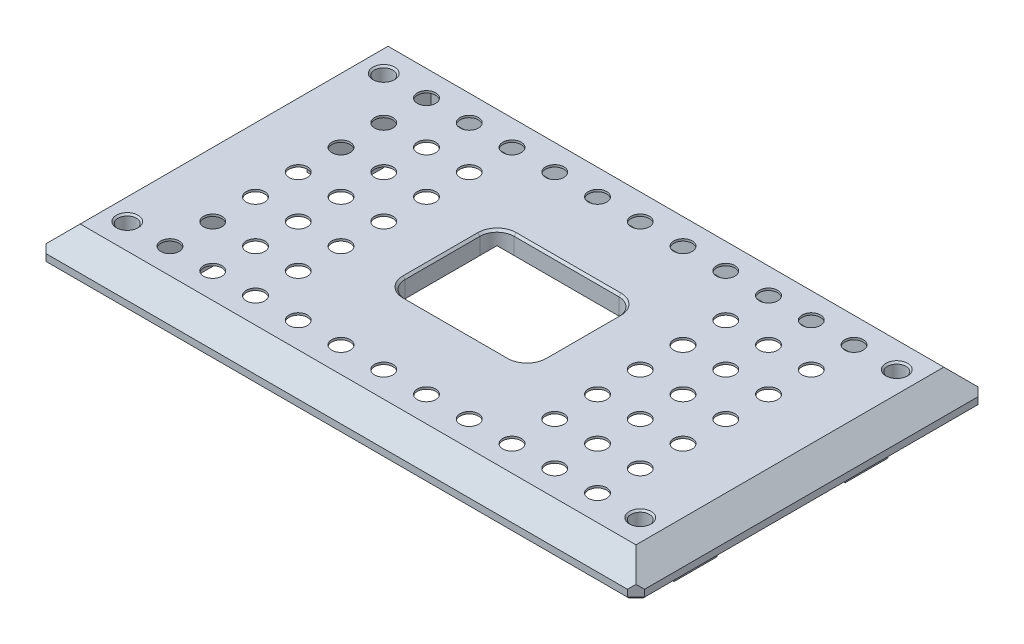
SolidWorks part; units mm, degrees
ref_plane "Front Plane" through (0, 0, 0) normal (0, 0, 1) x (1, 0, 0)
ref_plane "Top Plane" through (0, 0, 0) normal (0, 1, 0) x (1, 0, 0)
ref_plane "Right Plane" through (0, 0, 0) normal (1, 0, 0) x (0, 0, -1)
sketch "Sketch1" plane through (0, 0, 0) normal (0, 1, 0) x (1, 0, 0)
  line L1 (-70, -41) -> (70, -41)
  line L2 (-70, -41) -> (-70, 41)
  line L3 (-70, 41) -> (70, 41)
  line L4 (70, -41) -> (70, 41)
  line L5 (-70, -41) -> (70, 41) construction
  line L6 (-70, 41) -> (70, -41) construction
  point P0 (0, 0)
  dimension "D1" = 140
  dimension "D2" = 82
extrude "Boss-Extrude1" add sketch "Sketch1" along normal blind 2
sketch "Sketch2" plane through (0, 2, 0) normal (0, 1, 0) x (1, 0, 0)
  line L4 (70, -41) -> (70, 41)
  line L5 (70, 41) -> (-70, 41)
  line L6 (-70, 41) -> (-70, -41)
  line L7 (-70, -41) -> (70, -41)
  line L8 (70, -41) -> (70, 41)
  line L9 (70, 41) -> (-70, 41)
  line L10 (-70, 41) -> (-70, -41)
  line L11 (-70, -41) -> (70, -41)
  dimension "D1" = 0
ref_plane "Plane1" through (0, 7, 0) normal (0, 1, 0) x (1, 0, 0)
sketch "Sketch3" plane through (0, 7, 0) normal (0, 1, 0) x (1, 0, 0)
  line L0 (-70, 41) -> (-70, -41) construction
  line L1 (-65, -36) -> (65, -36)
  line L2 (-65, -36) -> (-65, 36)
  line L3 (-65, 36) -> (65, 36)
  line L4 (65, -36) -> (65, 36)
  line L5 (-65, -36) -> (65, 36) construction
  line L6 (-65, 36) -> (65, -36) construction
  line L7 (70, 41) -> (-70, 41) construction
  point P0 (0, 0)
  dimension "D1" = 5
  dimension "D2" = 5
loft "Loft1" add profiles "Sketch3", "Sketch2"
chamfer "Chamfer2" distance 2 angle 45 4 edges at (70, 1, 41) (70, 1, -41) (-70, 1, -41) (-70, 1, 41)
sketch "Sketch4" plane through (0, 0, 0) normal (0, -1, 0) x (1, 0, 0)
  line L0 (-70, -39) -> (-70, 39) construction
  line L1 (-62.9, 15) -> (-54.9, 15)
  line L2 (-62.9, 15) -> (-62.9, 25)
  line L3 (-62.9, 25) -> (-54.9, 25)
  line L4 (-54.9, 15) -> (-54.9, 25)
  line L5 (-62.9, 15) -> (-54.9, 25) construction
  line L6 (-62.9, 25) -> (-54.9, 15) construction
  line L7 (-70, 0) -> (70, 0) construction
  line L8 (70, 39) -> (70, -39) construction
  line L9 (0, 41) -> (0, -41) construction
  line L10 (-68, 41) -> (68, 41) construction
  line L11 (68, -41) -> (-68, -41) construction
  line L12 (-62.9, -25) -> (-54.9, -15) construction
  line L13 (-62.9, -15) -> (-54.9, -25) construction
  line L14 (-54.9, -15) -> (-54.9, -25)
  line L15 (-62.9, -25) -> (-54.9, -25)
  line L16 (-62.9, -15) -> (-62.9, -25)
  line L17 (-62.9, -15) -> (-54.9, -15)
  line L18 (62.9, -15) -> (54.9, -25) construction
  line L19 (62.9, -25) -> (54.9, -15) construction
  line L20 (62.9, 25) -> (54.9, 15) construction
  line L21 (62.9, 15) -> (54.9, 25) construction
  line L22 (62.9, -15) -> (54.9, -15)
  line L23 (62.9, -15) -> (62.9, -25)
  line L24 (62.9, -25) -> (54.9, -25)
  line L25 (54.9, -15) -> (54.9, -25)
  line L26 (54.9, 15) -> (54.9, 25)
  line L27 (62.9, 25) -> (54.9, 25)
  line L28 (62.9, 15) -> (62.9, 25)
  line L29 (62.9, 15) -> (54.9, 15)
  point P0 (-58.9, 20)
  point P21 (-58.9, -20)
  point P30 (58.9, -20)
  point P31 (58.9, 20)
  dimension "D1" = 10
  dimension "D2" = 7.1
  dimension "D3" = 8
  dimension "D4" = 40
extrude "Boss-Extrude2" add sketch "Sketch4" along normal blind 7
sketch "Sketch5" plane through (-62.9, 0, 0) normal (-1, 0, 0) x (0, 0, 1)
  line L0 (-15, 0) -> (-25, -7) construction
  line L1 (0, 0) -> (0, 50000) construction
  circle A0 centre (-20, -3.5) radius 2.05
  circle A1 centre (20, -3.5) radius 2.05
  dimension "D1" = 4.1
extrude "Cut-Extrude1" cut sketch "Sketch5" against normal through all
sketch "Sketch6" plane through (0, 0, 0) normal (0, -1, 0) x (1, 0, 0)
  line L0 (54.9, 25) -> (54.9, 15) construction
  line L1 (-53.9, -35) -> (53.9, -35)
  line L2 (-53.9, -35) -> (-53.9, 35)
  line L3 (-53.9, 35) -> (53.9, 35)
  line L4 (53.9, -35) -> (53.9, 35)
  line L5 (-53.9, -35) -> (53.9, 35) construction
  line L6 (-53.9, 35) -> (53.9, -35) construction
  line L8 (-65, 36) -> (65, 36) construction
  point P0 (0, 0)
  dimension "D1" = 1
  dimension "D2" = 1
extrude "Cut-Extrude2" cut sketch "Sketch6" against normal offset from surface (5.5 mm away) 1.5 up to face at (0, 7, 0)
sketch "Sketch7" plane through (0, 5.5, 0) normal (0, -1, 0) x (1, 0, 0)
  line L0 (0, 35) -> (0, -35) construction
  line L1 (-53.9, 35) -> (53.9, 35) construction
  line L2 (-53.9, -35) -> (53.9, -35) construction
  line L3 (-53.9, 0) -> (53.9, 0) construction
  line L4 (-53.9, -35) -> (-53.9, 35) construction
  line L5 (53.9, 35) -> (53.9, -35) construction
  circle A0 centre (0, 0) radius 2.15
  circle A1 centre (10, 0) radius 2.15
  circle A2 centre (20, 0) radius 2.15
  circle A3 centre (30, 0) radius 2.15
  circle A4 centre (40, 0) radius 2.15
  circle A5 centre (50, 0) radius 2.15
  circle A7 centre (10, 10) radius 2.15
  circle A8 centre (20, 10) radius 2.15
  circle A9 centre (30, 10) radius 2.15
  circle A10 centre (40, 10) radius 2.15
  circle A11 centre (50, 10) radius 2.15
  circle A13 centre (10, 20) radius 2.15
  circle A14 centre (20, 20) radius 2.15
  circle A15 centre (30, 20) radius 2.15
  circle A16 centre (40, 20) radius 2.15
  circle A17 centre (50, 20) radius 2.15
  circle A19 centre (10, 30) radius 2.15
  circle A20 centre (20, 30) radius 2.15
  circle A21 centre (30, 30) radius 2.15
  circle A22 centre (40, 30) radius 2.15
  circle A23 centre (50, 30) radius 2.15
  circle A25 centre (0, 10) radius 2.15
  circle A26 centre (0, 20) radius 2.15
  circle A27 centre (0, 30) radius 2.15
  circle A35 centre (-50, 30) radius 2.15
  circle A36 centre (-40, 30) radius 2.15
  circle A37 centre (-30, 30) radius 2.15
  circle A38 centre (-20, 30) radius 2.15
  circle A39 centre (-10, 30) radius 2.15
  circle A40 centre (-50, 20) radius 2.15
  circle A41 centre (-40, 20) radius 2.15
  circle A42 centre (-30, 20) radius 2.15
  circle A43 centre (-20, 20) radius 2.15
  circle A44 centre (-10, 20) radius 2.15
  circle A45 centre (-50, 10) radius 2.15
  circle A46 centre (-40, 10) radius 2.15
  circle A47 centre (-30, 10) radius 2.15
  circle A48 centre (-20, 10) radius 2.15
  circle A49 centre (-10, 10) radius 2.15
  circle A50 centre (-50, 0) radius 2.15
  circle A51 centre (-40, 0) radius 2.15
  circle A52 centre (-30, 0) radius 2.15
  circle A53 centre (-20, 0) radius 2.15
  circle A54 centre (-10, 0) radius 2.15
  circle A55 centre (-10, -10) radius 2.15
  circle A56 centre (-20, -10) radius 2.15
  circle A57 centre (-30, -10) radius 2.15
  circle A58 centre (-40, -10) radius 2.15
  circle A59 centre (-50, -10) radius 2.15
  circle A60 centre (-10, -20) radius 2.15
  circle A61 centre (-20, -20) radius 2.15
  circle A62 centre (-30, -20) radius 2.15
  circle A63 centre (-40, -20) radius 2.15
  circle A64 centre (-50, -20) radius 2.15
  circle A65 centre (-10, -30) radius 2.15
  circle A66 centre (-20, -30) radius 2.15
  circle A67 centre (-30, -30) radius 2.15
  circle A68 centre (-40, -30) radius 2.15
  circle A69 centre (-50, -30) radius 2.15
  circle A70 centre (0, -30) radius 2.15
  circle A71 centre (0, -20) radius 2.15
  circle A72 centre (0, -10) radius 2.15
  circle A73 centre (50, -30) radius 2.15
  circle A74 centre (40, -30) radius 2.15
  circle A75 centre (30, -30) radius 2.15
  circle A76 centre (20, -30) radius 2.15
  circle A77 centre (10, -30) radius 2.15
  circle A78 centre (50, -20) radius 2.15
  circle A79 centre (40, -20) radius 2.15
  circle A80 centre (30, -20) radius 2.15
  circle A81 centre (20, -20) radius 2.15
  circle A82 centre (10, -20) radius 2.15
  circle A83 centre (50, -10) radius 2.15
  circle A84 centre (40, -10) radius 2.15
  circle A85 centre (30, -10) radius 2.15
  circle A86 centre (20, -10) radius 2.15
  circle A87 centre (10, -10) radius 2.15
  dimension "D1" = 4.3
  dimension "D2" = 6
  dimension "D3" = 4
extrude "Cut-Extrude3" cut sketch "Sketch7" against normal through all
sketch "Sketch8" plane through (0, 5.5, 0) normal (0, -1, 0) x (1, 0, 0)
  line L0 (0, 35) -> (0, -35) construction
  line L1 (-53.9, 35) -> (53.9, 35) construction
  line L2 (53.9, -35) -> (-53.9, -35) construction
  line L3 (-53.9, 0) -> (53.9, 0) construction
  line L4 (-53.9, -35) -> (-53.9, 35) construction
  line L5 (53.9, -35) -> (53.9, 35) construction
  circle A0 centre (0, 0) radius 4.2
  circle A1 centre (10, 0) radius 4.2
  circle A2 centre (20, 0) radius 4.2
  circle A3 centre (30, 0) radius 4.2
  circle A4 centre (40, 0) radius 4.2
  circle A5 centre (50, 0) radius 4.2
  circle A6 centre (10, 10) radius 4.2
  circle A7 centre (20, 10) radius 4.2
  circle A8 centre (30, 10) radius 4.2
  circle A9 centre (40, 10) radius 4.2
  circle A10 centre (50, 10) radius 4.2
  circle A11 centre (10, 20) radius 4.2
  circle A12 centre (20, 20) radius 4.2
  circle A13 centre (30, 20) radius 4.2
  circle A14 centre (40, 20) radius 4.2
  circle A15 centre (50, 20) radius 4.2
  circle A16 centre (10, 30) radius 4.2
  circle A17 centre (20, 30) radius 4.2
  circle A18 centre (30, 30) radius 4.2
  circle A19 centre (40, 30) radius 4.2
  circle A20 centre (50, 30) radius 4.2
  circle A21 centre (0, 10) radius 4.2
  circle A22 centre (0, 20) radius 4.2
  circle A23 centre (0, 30) radius 4.2
  circle A24 centre (0, -30) radius 4.2
  circle A25 centre (0, -20) radius 4.2
  circle A26 centre (0, -10) radius 4.2
  circle A27 centre (50, -30) radius 4.2
  circle A28 centre (40, -30) radius 4.2
  circle A29 centre (30, -30) radius 4.2
  circle A30 centre (20, -30) radius 4.2
  circle A31 centre (10, -30) radius 4.2
  circle A32 centre (50, -20) radius 4.2
  circle A33 centre (40, -20) radius 4.2
  circle A34 centre (30, -20) radius 4.2
  circle A35 centre (20, -20) radius 4.2
  circle A36 centre (10, -20) radius 4.2
  circle A37 centre (50, -10) radius 4.2
  circle A38 centre (40, -10) radius 4.2
  circle A39 centre (30, -10) radius 4.2
  circle A40 centre (20, -10) radius 4.2
  circle A41 centre (10, -10) radius 4.2
  circle A42 centre (-10, -10) radius 4.2
  circle A43 centre (-20, -10) radius 4.2
  circle A44 centre (-30, -10) radius 4.2
  circle A45 centre (-40, -10) radius 4.2
  circle A46 centre (-50, -10) radius 4.2
  circle A47 centre (-10, -20) radius 4.2
  circle A48 centre (-20, -20) radius 4.2
  circle A49 centre (-30, -20) radius 4.2
  circle A50 centre (-40, -20) radius 4.2
  circle A51 centre (-50, -20) radius 4.2
  circle A52 centre (-10, -30) radius 4.2
  circle A53 centre (-20, -30) radius 4.2
  circle A54 centre (-30, -30) radius 4.2
  circle A55 centre (-40, -30) radius 4.2
  circle A56 centre (-50, -30) radius 4.2
  circle A57 centre (-50, 30) radius 4.2
  circle A58 centre (-40, 30) radius 4.2
  circle A59 centre (-30, 30) radius 4.2
  circle A60 centre (-20, 30) radius 4.2
  circle A61 centre (-10, 30) radius 4.2
  circle A62 centre (-50, 20) radius 4.2
  circle A63 centre (-40, 20) radius 4.2
  circle A64 centre (-30, 20) radius 4.2
  circle A65 centre (-20, 20) radius 4.2
  circle A66 centre (-10, 20) radius 4.2
  circle A67 centre (-50, 10) radius 4.2
  circle A68 centre (-40, 10) radius 4.2
  circle A69 centre (-30, 10) radius 4.2
  circle A70 centre (-20, 10) radius 4.2
  circle A71 centre (-10, 10) radius 4.2
  circle A72 centre (-50, 0) radius 4.2
  circle A73 centre (-40, 0) radius 4.2
  circle A74 centre (-30, 0) radius 4.2
  circle A75 centre (-20, 0) radius 4.2
  circle A76 centre (-10, 0) radius 4.2
  dimension "D1" = 8.4
  dimension "D2" = 6
  dimension "D3" = 4
extrude "Cut-Extrude4" cut sketch "Sketch8" against normal blind 1
sketch "Sketch9" plane through (0, 7, 0) normal (0, 1, 0) x (1, 0, 0)
  line L1 (53.9, -35) -> (34.6, -35)
  line L2 (53.9, -35) -> (53.9, -15.5)
  line L3 (53.9, -15.5) -> (34.6, -15.5)
  line L4 (34.6, -35) -> (34.6, -15.5)
  dimension "D1" = 19.3
  dimension "D2" = 19.5
sketch "Sketch13" plane through (0, 5.5, 0) normal (0, -1, 0) x (1, 0, 0)
  circle A0 centre (50, 20) radius 4.2 construction
  circle A1 centre (40, 20) radius 4.2 construction
  circle A2 centre (40, 30) radius 4.2 construction
  circle A3 centre (50, 30) radius 4.2 construction
  circle A4 centre (50, 20) radius 4.2
  circle A5 centre (40, 20) radius 4.2
  circle A6 centre (40, 30) radius 4.2
  circle A7 centre (50, 30) radius 4.2
extrude "Boss-Extrude4" [suppressed] add sketch "Sketch13" against normal up to surface (1.5 mm away)
sketch "Sketch10" plane through (0, 5.5, 0) normal (0, -1, 0) x (1, 0, 0)
  line L1 (53.9, 35) -> (43.9, 35) construction
  line L2 (53.9, 35) -> (53.9, 25) construction
  line L3 (53.9, 25) -> (43.9, 25) construction
  line L4 (43.9, 35) -> (43.9, 25) construction
  circle A0 centre (43.9, 25) radius 3.3
  dimension "D1" = 6.6
  dimension "D2" = 10
extrude "Cut-Extrude5" [suppressed] cut sketch "Sketch10" against normal through all
sketch "Sketch11" plane through (0, 0, 0) normal (0, -1, 0) x (1, 0, 0)
  line L0 (53.9, 35) -> (53.9, 31.5588) construction
  line L1 (53.9, 10) -> (63.9, 10)
  line L2 (53.9, 10) -> (53.9, -10)
  line L3 (53.9, -10) -> (63.9, -10)
  line L4 (63.9, 10) -> (63.9, -10)
  line L5 (-53.9, 35) -> (-53.9, -35) construction
  line L6 (-53.9, 10) -> (-63.9, 10)
  line L7 (-53.9, 10) -> (-53.9, -10)
  line L8 (-53.9, -10) -> (-63.9, -10)
  line L9 (-63.9, 10) -> (-63.9, -10)
  line L10 (-70, -39) -> (-70, 39) construction
  point P12 (-63.9, 0)
  point P15 (-70, 0)
  point P16 (63.9, 0)
  dimension "D1" = 10
  dimension "D2" = 20
extrude "Cut-Extrude6" cut sketch "Sketch11" against normal up to surface (5.5 mm away) up to face at (10, 5.5, -5.8)
sketch "Sketch12" plane through (0, 0, 0) normal (0, -1, 0) x (1, 0, 0)
  line L0 (0, 0) -> (-60, 0) construction
  line L1 (-60, -30) -> (-60, 30) construction
  line L2 (-70, -39) -> (-70, 39) construction
  line L3 (0, 41) -> (0, -41) construction
  line L4 (-68, 41) -> (68, 41) construction
  line L5 (68, -41) -> (-68, -41) construction
  line L6 (60, -30) -> (60, 30) construction
  circle A0 centre (-60, 30) radius 2.15
  circle A1 centre (-60, -30) radius 2.15
  circle A2 centre (60, -30) radius 2.15
  circle A3 centre (60, 30) radius 2.15
  point P6 (-60, 0)
  point P20 (60, 0)
  dimension "D1" = 4.3
  dimension "D2" = 60
  dimension "D3" = 10
extrude "Cut-Extrude7" cut sketch "Sketch12" against normal through all
chamfer "Chamfer3" distance 0.4 angle 45 8 edges at (-69, 0, -40) (-70, 0, 0) (-69, 0, 40) (0, 0, 41) (69, 0, 40) (70, 0, 0) (69, 0, -40) (0, 0, -41)
chamfer "Chamfer4" distance 0.4 angle 45 4 edges at (60, 7, 27.85) (60, 7, -32.15) (-60, 7, 27.85) (-60, 7, -32.15)
chamfer "Chamfer5" distance 0.4 angle 45 4 edges at (-62.9, -3.5, 17.95) (-62.9, -3.5, -17.95) (62.9, -3.5, 22.05) (62.9, -3.5, -17.95)
sketch "Sketch14" plane through (0, 5.5, 0) normal (0, -1, 0) x (1, 0, 0)
  line L1 (-25, -25) -> (25, -25)
  line L2 (-25, -25) -> (-25, 25)
  line L3 (-25, 25) -> (25, 25)
  line L4 (25, -25) -> (25, 25)
  line L5 (-25, -25) -> (25, 25) construction
  line L6 (-25, 25) -> (25, -25) construction
  point P0 (0, 0)
  dimension "D1" = 50
  dimension "D2" = 50
extrude "Boss-Extrude5" add sketch "Sketch14" against normal up to surface (1.5 mm away) up to face at (60, 7, 27.45)
sketch "Sketch18" plane through (0, 5.5, 0) normal (0, -1, 0) x (1, 0, 0)
  line L1 (-22.5, -20) -> (22.5, -20)
  line L2 (-22.5, -20) -> (-22.5, 20)
  line L3 (-22.5, 20) -> (22.5, 20)
  line L4 (22.5, -20) -> (22.5, 20)
  line L5 (-22.5, -20) -> (22.5, 20) construction
  line L6 (-22.5, 20) -> (22.5, -20) construction
  point P0 (0, 0)
  dimension "D1" = 40
  dimension "D2" = 45
extrude "Boss-Extrude6" add sketch "Sketch18" along normal blind 3.5
sketch "Sketch17" plane through (0, 7, 0) normal (0, 1, 0) x (1, 0, 0)
  line L1 (-18.21, -14.785) -> (18.21, -14.785) construction
  line L2 (-18.21, -14.785) -> (-18.21, 14.785) construction
  line L3 (-18.21, 14.785) -> (18.21, 14.785) construction
  line L4 (18.21, -14.785) -> (18.21, 14.785) construction
  line L5 (-18.21, -14.785) -> (18.21, 14.785) construction
  line L6 (-18.21, 14.785) -> (18.21, -14.785) construction
  line L7 (-16.25, -12.75) -> (16.25, -12.75)
  line L8 (-16.25, -12.75) -> (-16.25, 12.75)
  line L9 (-16.25, 12.75) -> (16.25, 12.75)
  line L10 (16.25, -12.75) -> (16.25, 12.75)
  line L11 (-16.25, -12.75) -> (16.25, 12.75) construction
  line L12 (-16.25, 12.75) -> (16.25, -12.75) construction
  circle A0 centre (-18.21, 14.785) radius 1.35
  circle A1 centre (18.21, 14.785) radius 1.35
  circle A2 centre (18.21, -14.785) radius 1.35
  circle A3 centre (-18.21, -14.785) radius 1.35
  point P0 (0, 0)
  point P10 (0, 0)
  dimension "D3" = 2.7
  dimension "D1" = 36.42
  dimension "D2" = 29.57
  dimension "D4" = 25.5
  dimension "D5" = 32.5
extrude "Cut-Extrude8" cut sketch "Sketch17" against normal through all
chamfer "Chamfer6" distance 0.6 angle 45 4 edges at (16.25, 2, 0) (0, 2, 12.75) (-16.25, 2, 0) (0, 2, -12.75)
fillet "Fillet1" radius 4 4 edges at (-16.25, 4.8, 12.75) (16.25, 4.8, 12.75) (16.25, 4.8, -12.75) (-16.25, 4.8, -12.75)
chamfer "Chamfer7" distance 0.5 angle 45 8 edges at (16.25, 7, 0) (15.0784, 7, -11.5784) (15.0784, 7, 11.5784) (0, 7, -12.75) (0, 7, 12.75) (-15.0784, 7, -11.5784) (-15.0784, 7, 11.5784) (-16.25, 7, 0)
sketch "Sketch19" plane through (0, 7, 0) normal (0, 1, 0) x (1, 0, 0)
  circle A0 centre (-18.21, 14.785) radius 1.35
  circle A1 centre (18.21, 14.785) radius 1.35
  circle A2 centre (18.21, -14.785) radius 1.35
  circle A3 centre (-18.21, -14.785) radius 1.35
  circle A4 centre (-18.21, 14.785) radius 1.35 construction
extrude "Boss-Extrude7" add sketch "Sketch19" against normal blind 1
sketch "Sketch20" plane through (0, 2, 0) normal (0, -1, 0) x (1, 0, 0)
  circle A0 centre (-18.21, 14.785) radius 1.8
  circle A1 centre (18.21, 14.785) radius 1.8
  circle A2 centre (18.21, -14.785) radius 1.8
  circle A3 centre (-18.21, -14.785) radius 1.8
  dimension "D1" = 3.6
extrude "Cut-Extrude9" cut sketch "Sketch20" against normal up to surface (4 mm away)
chamfer "Chamfer8" distance 2 angle 45 4 edges at (22.5, 2, 0) (0, 2, -20) (0, 2, 20) (-22.5, 2, 0)
